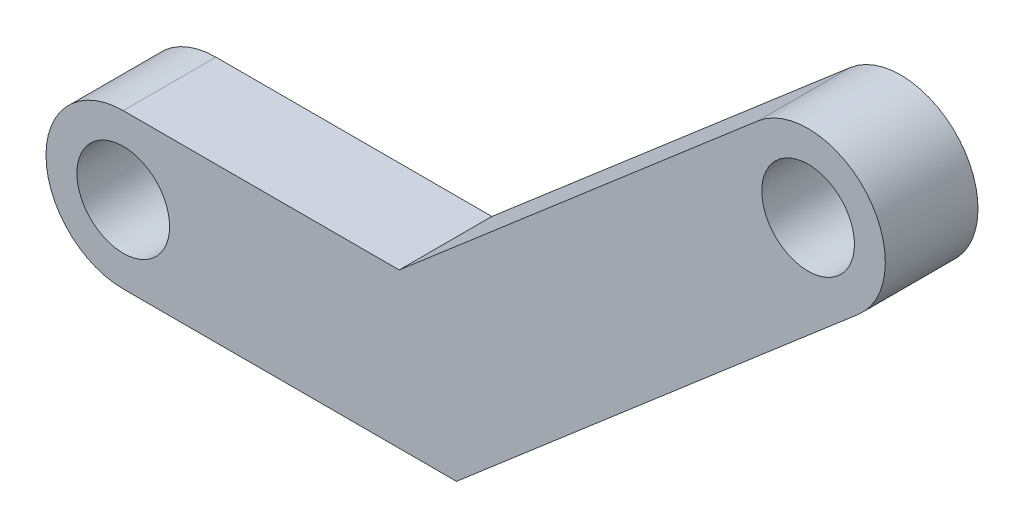
SolidWorks part; units mm, degrees
ref_plane "Front Plane" through (0, 0, 0) normal (0, 0, 1) x (1, 0, 0)
ref_plane "Top Plane" through (0, 0, 0) normal (0, 1, 0) x (1, 0, 0)
ref_plane "Right Plane" through (0, 0, 0) normal (1, 0, 0) x (0, 0, -1)
sketch "Sketch1" plane through (0, 0, 0) normal (0, 0, 1) x (1, 0, 0)
  line L0 (91.9888, 116.5225) -> (-31.1112, 10.6772) construction
  line L1 (-31.1112, 10.6772) -> (-129.7112, 10.6772) construction
  line L2 (75.6897, 135.4787) -> (-40.3813, 35.6772)
  line L3 (-40.3813, 35.6772) -> (-129.7112, 35.6772)
  line L4 (108.288, 97.5663) -> (-21.841, -14.3228)
  line L5 (-21.841, -14.3228) -> (-129.7112, -14.3228)
  arc A0 (75.6897, 135.4787) -> (108.288, 97.5663) centre (91.9888, 116.5225) cw
  arc A1 (-129.7112, 35.6772) -> (-129.7112, -14.3228) centre (-129.7112, 10.6772) ccw
  circle A2 centre (91.9888, 116.5225) radius 15
  circle A3 centre (-129.7112, 10.6772) radius 15
  dimension "D1" = 139.31
  dimension "D2" = 123.1
  dimension "D3" = 98.6
  dimension "D4" = 25
  dimension "D5" = 25
extrude "Boss-Extrude1" add sketch "Sketch1" along normal blind 30
